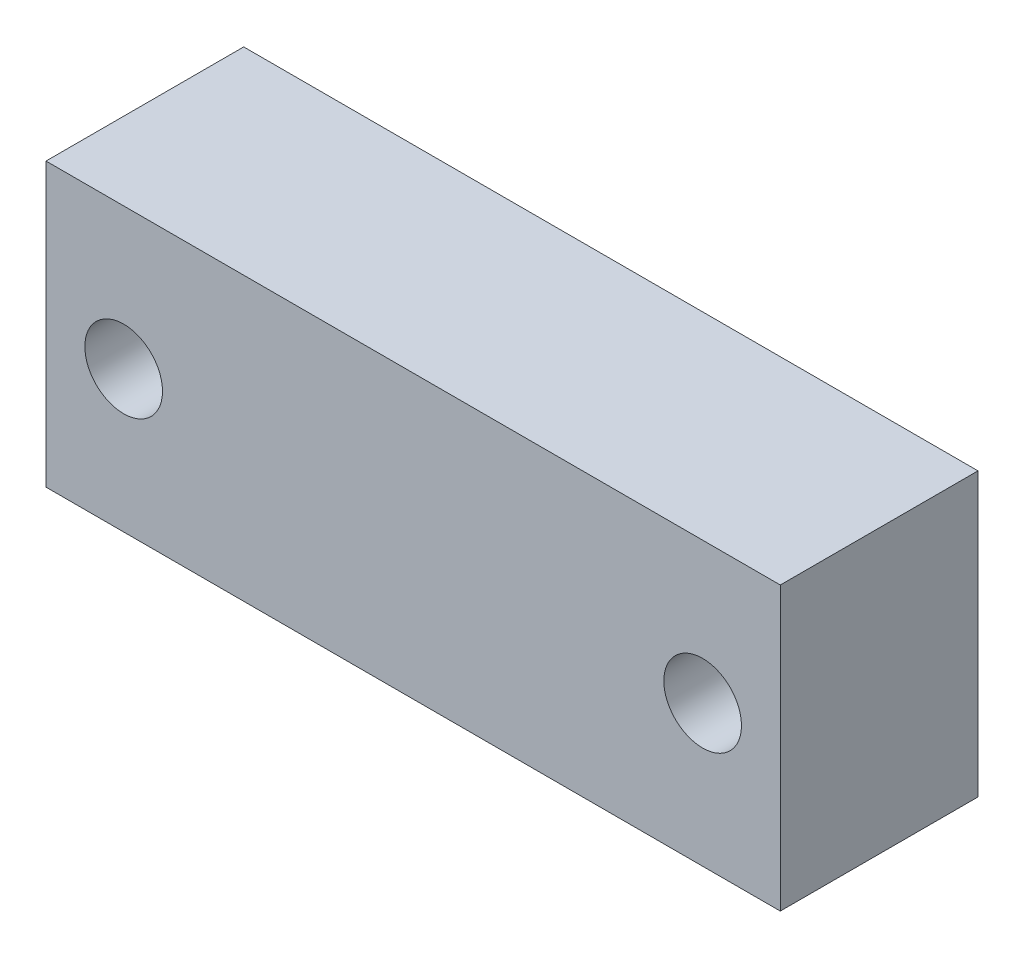
SolidWorks part; units mm, degrees
ref_plane "정면" through (0, 0, 0) normal (0, 0, 1) x (1, 0, 0)
ref_plane "윗면" through (0, 0, 0) normal (0, 1, 0) x (1, 0, 0)
ref_plane "우측면" through (0, 0, 0) normal (1, 0, 0) x (0, 0, -1)
sketch "스케치1" plane through (0, 0, 0) normal (0, 0, 1) x (1, 0, 0)
  line L1 (-26, 10) -> (26, 10)
  line L2 (-26, 10) -> (-26, -10)
  line L3 (-26, -10) -> (26, -10)
  line L4 (26, 10) -> (26, -10)
  line L5 (-26, 10) -> (26, -10) construction
  line L6 (-26, -10) -> (26, 10) construction
  point P0 (0, 0)
  dimension "D1" = 20
  dimension "D2" = 52
extrude "보스-돌출1" add sketch "스케치1" along normal blind 14
hole_wizard "M5 여유 구멍1" positions "스케치2" profile "스케치3" hole size "M5" standard "KS" end condition through all
sketch "스케치2" plane through (0, 0, 14) normal (0, 0, 1) x (1, 0, 0)
  line L0 (-26, -10) -> (26, -10) construction
  point P0 (-20.5, 0)
  point P2 (20.5, 0)
  point P9 (-19.1199, 1.2246)
  dimension "D1" = 41
  dimension "D2" = 20.5
  dimension "D3" = 10
sketch "스케치3" plane through (-20.5, 0, 14) normal (1, 0, 0) x (0, -1, 0)
  line L0 (0, 0) -> (0, 14)
  line L1 (0, 14) -> (2.75, 14)
  line L2 (2.75, 14) -> (2.75, 0)
  line L5 (2.75, 0) -> (0, 0)
  line L11 (0, -6.35) -> (0, 107.95) construction
  dimension "관통 구멍 지름" = 5.5
  dimension "관통 구멍 깊이" = 14
